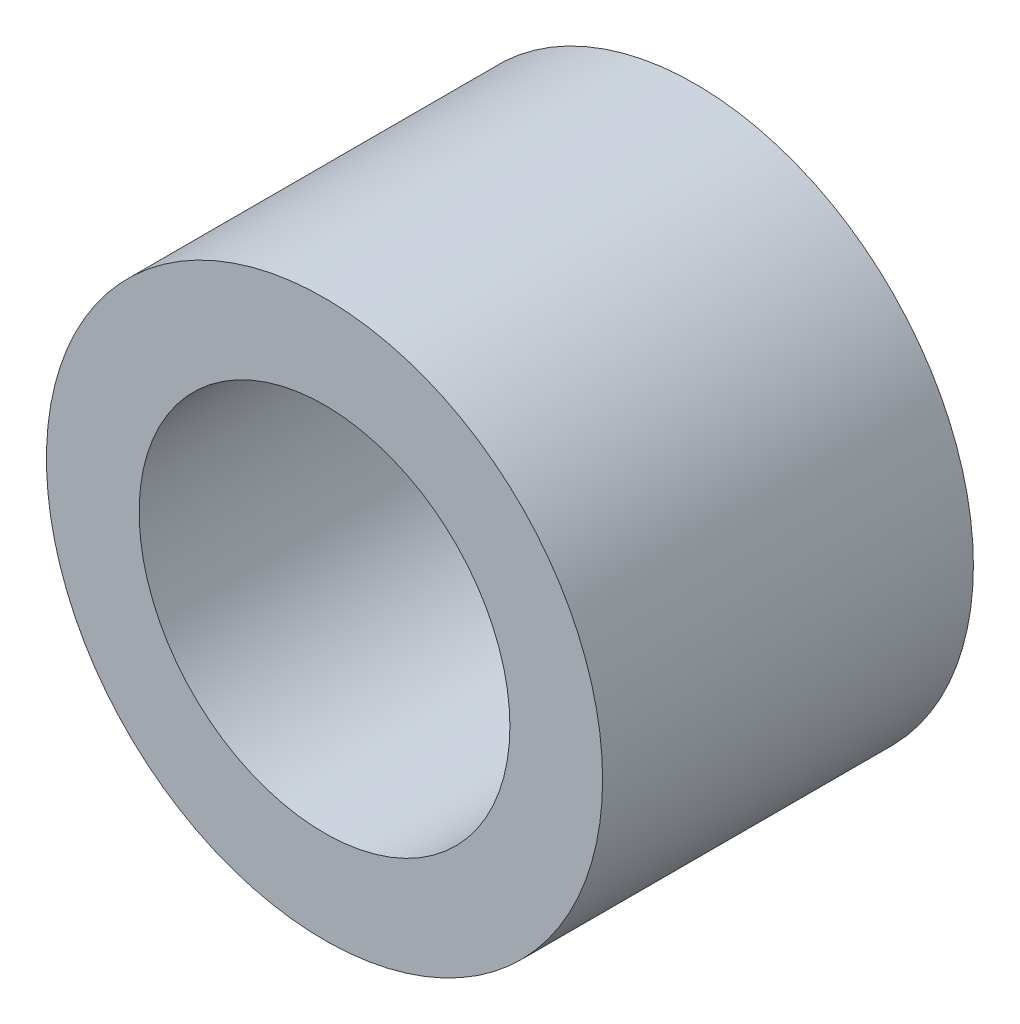
SolidWorks part; units mm, degrees
ref_plane "前视基准面" through (0, 0, 0) normal (0, 0, 1) x (1, 0, 0)
ref_plane "上视基准面" through (0, 0, 0) normal (0, 1, 0) x (1, 0, 0)
ref_plane "右视基准面" through (0, 0, 0) normal (1, 0, 0) x (0, 0, -1)
sketch "草图1" plane through (0, 0, 0) normal (0, 0, 1) x (1, 0, 0)
  circle A0 centre (0, 0) radius 3
  circle A1 centre (0, 0) radius 2
  dimension "D1" = 6
  dimension "D2" = 4
extrude "凸台-拉伸1" add sketch "草图1" along normal mid plane 4
